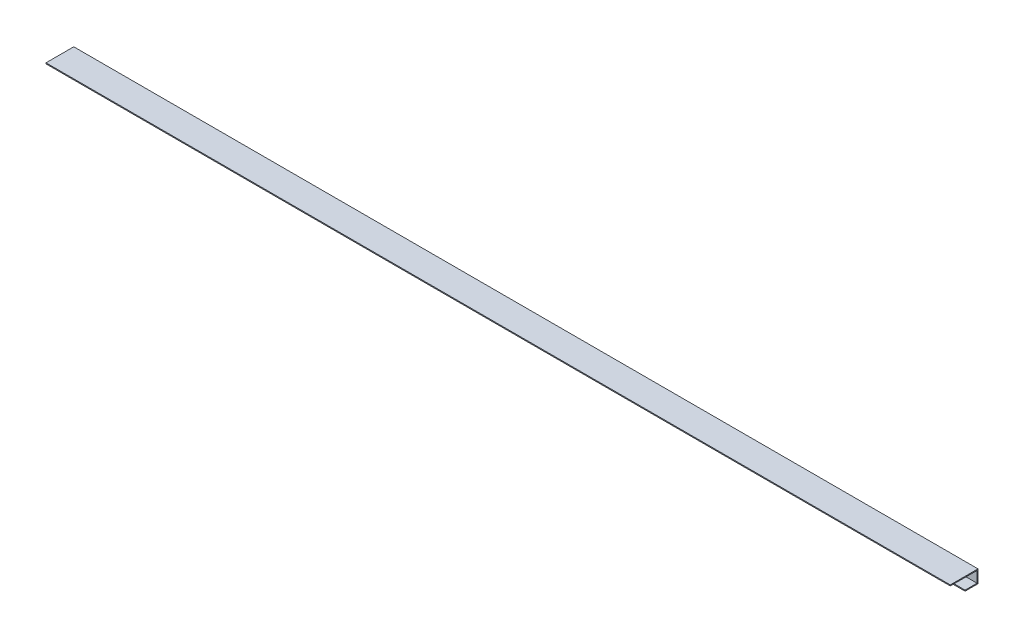
SolidWorks part; units mm, degrees
ref_plane "Front Plane" through (0, 0, 0) normal (0, 0, 1) x (1, 0, 0)
ref_plane "Top Plane" through (0, 0, 0) normal (0, 1, 0) x (1, 0, 0)
ref_plane "Right Plane" through (0, 0, 0) normal (1, 0, 0) x (0, 0, -1)
sketch "Sketch1" plane through (0, 0, 0) normal (1, 0, 0) x (0, 0, -1)
  line L0 (0, 0) -> (58, 0)
  line L1 (58, 0) -> (58, -27)
  line L2 (58, -27) -> (31, -27)
  line L3 (0, -2) -> (56, -2)
  line L4 (56, -2) -> (56, -25)
  line L5 (56, -25) -> (31, -25)
  line L6 (0, 0) -> (0, -2)
  line L7 (31, -25) -> (31, -27)
  dimension "D1" = 2
  dimension "D2" = 58
  dimension "D3" = 27
  dimension "D4" = 27
extrude "Boss-Extrude1" add sketch "Sketch1" along normal blind 1890
equation "\"door_base_short7_BL_Single_height\"=1890.0"
equation "\"D1@Boss-Extrude1\"=\"door_base_short7_BL_Single_height\""
equation "\"CarBeamWidth\"=700.0"
equation "\"WheelWidth\"=650.0"
equation "\"Wheel_FrontBoxDistance\"=1390.0"
equation "\"boxLength\"=5100.0"
equation "\"boxWidth\"=1930.0"
equation "\"MetalSheet_3mm_length\"=5030.0"
equation "\"MetalSheet_3mm_width\"=1923.0"
equation "\"MetalSheet_3mm_FloorCut_L_length\"=1764.0"
equation "\"MetalSheet_3mm_FloorCut_L_disdance\"=1665.0"
equation "\"MetalSheet_3mm_FloorCut_R_length\"=1764.0"
equation "\"MetalSheet_3mm_FloorCut_R_disdance\"=1665.0"
equation "\"indoorHeight\"=1940.0"
equation "\"indoorHeight_para\"=25.0"
equation "\"rearLightHeight_para\"=265.0"
equation "\"haveDoor_R\"=1"
equation "\"side_door_bottom_R_3mm_length\"=1934.0"
equation "\"side_door_bottom_R_3mm_toFrontDistance\"=1583.0"
equation "\"1Bar_Side_RF_3mm_length\"=1493.0"
equation "\"1Bar_Side_RB_3mm_length\"=1493.0"
equation "\"DoorSeparator_RF_3mm_withHinge_toFrontDistance\"=1673.0"
equation "\"DoorSeparator_RF_3mm_withHinge_exist\"=1"
equation "\"DoorSeparator_RB_3mm_withHinge_toFrontDistance\"=3427.0"
equation "\"DoorSeparator_RB_3mm_withHinge_exist\"=1"
equation "\"Door_R1_L_open_Single_toFrontDistance\"=2547.5"
equation "\"Door_R1_L_open_Single_exist\"=1"
equation "\"door_base_long7_R1_L_open_Single_height\"=1890.0"
equation "\"door_base_short7_R1_L_open_Single_height\"=1890.0"
equation "\"door_base_short7_R1_L_open_Single_width\"=864"
equation "\"Door_R1_R_open_Single_toFrontDistance\"=3422.0"
equation "\"Door_R1_R_open_Single_exist\"=1"
equation "\"door_base_long7_R1_R_open_Single_height\"=1890.0"
equation "\"door_base_short7_R1_R_open_Single_height\"=1890.0"
equation "\"door_base_short7_R1_R_open_Single_width\"=864"
equation "\"x\"=66.0"
equation "\"door_base_double_BL_height\"=1890.0"
equation "\"door_base_short7_BL_Single_width\"=864"
equation "\"door_base_long7_BR_Single_height\"=1890.0"
equation "\"door_base_short7_BR_Single_height\"=1890.0"
equation "\"door_base_short7_BR_Single_width\"=864"
equation "\"da\"=62.0"
equation "\"SquareTube_length\"=1923.0"
equation "\"channelSteel_length\"=5030.0"
equation "\"SquareTube_inFront_AvgDistance\"=285.0"
equation "\"SquareTube_inFront_TotalCount\"=5"
equation "\"SquareTube_inFront1_cutDepth50_R\"=0.5"
equation "\"SquareTube_inFront1_cutDepth50_L\"=0.5"
equation "\"SquareTube_inFront2_cutDepth50_R\"=0.5"
equation "\"SquareTube_inFront2_cutDepth50_L\"=0.5"
equation "\"SquareTube_inFront3_cutDepth50_R\"=0.5"
equation "\"SquareTube_inFront3_cutDepth50_L\"=0.5"
equation "\"SquareTube_inFront4_cutDepth50_R\"=0.5"
equation "\"SquareTube_inFront4_cutDepth50_L\"=0.5"
equation "\"SquareTube_inFront5_cutDepth50_R\"=50"
equation "\"SquareTube_inFront5_cutDepth50_L\"=50"
equation "\"SquareTube_inFront6_cutDepth50_R\"=50"
equation "\"SquareTube_inFront6_cutDepth50_L\"=50"
equation "\"SquareTube_inFront7_cutDepth50_R\"=50"
equation "\"SquareTube_inFront7_cutDepth50_L\"=50"
equation "\"SquareTube_inFront8_cutDepth50_R\"=50"
equation "\"SquareTube_inFront8_cutDepth50_L\"=50"
equation "\"SquareTube_inFront9_cutDepth50_R\"=50"
equation "\"SquareTube_inFront9_cutDepth50_L\"=50"
equation "\"SquareTube_inFront10_cutDepth50_R\"=50"
equation "\"SquareTube_inFront10_cutDepth50_L\"=50"
equation "\"SquareTube_inFront11_cutDepth50_R\"=50"
equation "\"SquareTube_inFront11_cutDepth50_L\"=50"
equation "\"SquareTube_inFront12_cutDepth50_R\"=50"
equation "\"SquareTube_inFront12_cutDepth50_L\"=50"
equation "\"SquareTube_inFront13_cutDepth50_R\"=50"
equation "\"SquareTube_inFront13_cutDepth50_L\"=50"
equation "\"SquareTube_inFront14_cutDepth50_R\"=50"
equation "\"SquareTube_inFront14_cutDepth50_L\"=50"
equation "\"SquareTube_inBack_AvgDistance\"=333.125"
equation "\"SquareTube_inBack_TotalCount\"=9"
equation "\"SquareTube_inBack1_cutDepth50_R\"=50"
equation "\"SquareTube_inBack1_cutDepth50_L\"=50"
equation "\"SquareTube_inBack2_cutDepth50_R\"=50"
equation "\"SquareTube_inBack2_cutDepth50_L\"=50"
equation "\"SquareTube_inBack3_cutDepth50_R\"=50"
equation "\"SquareTube_inBack3_cutDepth50_L\"=50"
equation "\"SquareTube_inBack4_cutDepth50_R\"=50"
equation "\"SquareTube_inBack4_cutDepth50_L\"=50"
equation "\"SquareTube_inBack5_cutDepth50_R\"=50"
equation "\"SquareTube_inBack5_cutDepth50_L\"=50"
equation "\"SquareTube_inBack6_cutDepth50_R\"=0.5"
equation "\"SquareTube_inBack6_cutDepth50_L\"=0.5"
equation "\"SquareTube_inBack7_cutDepth50_R\"=0.5"
equation "\"SquareTube_inBack7_cutDepth50_L\"=0.5"
equation "\"SquareTube_inBack8_cutDepth50_R\"=0.5"
equation "\"SquareTube_inBack8_cutDepth50_L\"=0.5"
